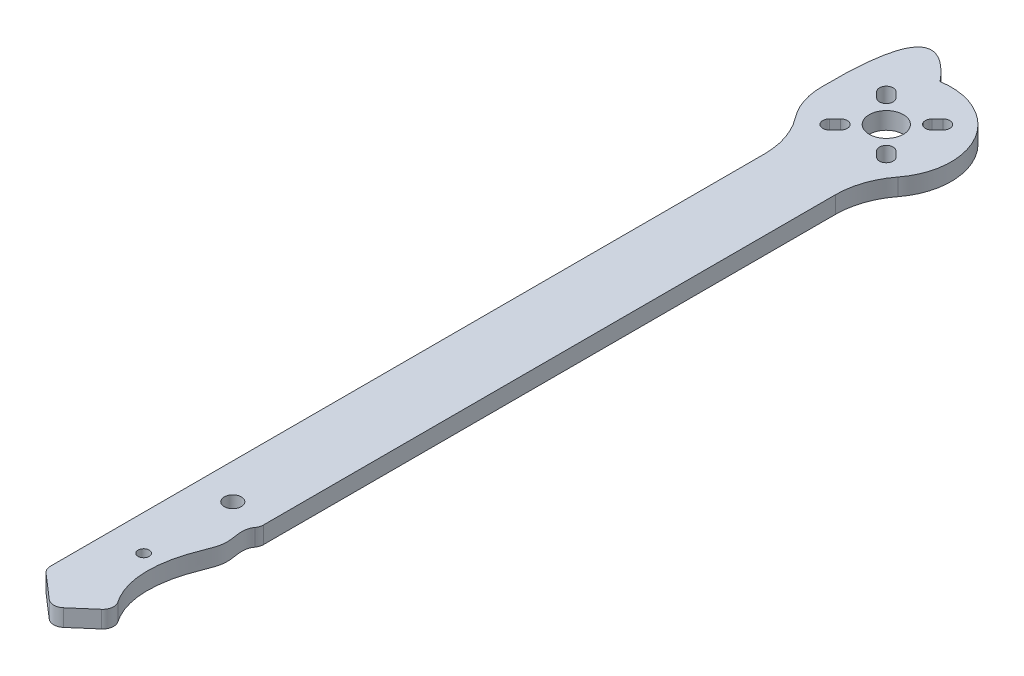
SolidWorks part; units mm, degrees
ref_plane "Front Plane" through (0, 0, 0) normal (0, 0, 1) x (1, 0, 0)
ref_plane "Top Plane" through (0, 0, 0) normal (0, 1, 0) x (1, 0, 0)
ref_plane "Right Plane" through (0, 0, 0) normal (1, 0, 0) x (0, 0, -1)
sketch "Sketch1" plane through (0, 0, 0) normal (0, 1, 0) x (1, 0, 0)
  line L0 (0, 0) -> (0, 209.55)
  line L1 (5.332, 189.1367) -> (6.5949, 187.8739) construction
  line L3 (-8.2352, 181.8344) -> (-8.2352, 0)
  line L4 (-8.2352, 0) -> (8.2352, 0)
  line L5 (8.2352, 181.8344) -> (8.2352, 0)
  line L6 (-6.4546, 190.2593) -> (-7.7174, 188.9964)
  line L7 (6.4546, 190.2593) -> (7.7174, 188.9964)
  line L8 (4.2095, 188.0142) -> (5.4723, 186.7513)
  line L9 (-4.2095, 188.0142) -> (-5.4723, 186.7513)
  line L10 (-5.332, 189.1367) -> (-6.5949, 187.8739) construction
  line L11 (-4.2095, 200.9233) -> (-5.4723, 202.1862)
  line L12 (-6.4546, 198.6782) -> (-7.7174, 199.9411)
  line L13 (-5.332, 199.8008) -> (-6.5949, 201.0636) construction
  line L14 (6.4546, 198.6782) -> (7.7174, 199.9411)
  line L15 (4.2095, 200.9233) -> (5.4723, 202.1862)
  line L16 (5.332, 199.8008) -> (6.5949, 201.0636) construction
  line L17 (-8.2352, 7.1437) -> (0, 0)
  line L18 (8.2352, 7.1437) -> (0, 0)
  line L19 (-8.2352, 7.1437) -> (8.2352, 7.1437)
  circle A0 centre (0, 194.4688) radius 3.9687
  circle A1 centre (0, 194.4688) radius 15.0812
  arc A2 (6.4546, 190.2593) -> (4.2095, 188.0142) centre (5.332, 189.1367) ccw
  arc A3 (5.4723, 186.7513) -> (7.7174, 188.9964) centre (6.5949, 187.8739) ccw
  arc A4 (-4.2095, 188.0142) -> (-6.4546, 190.2593) centre (-5.332, 189.1367) ccw
  arc A5 (-7.7174, 188.9964) -> (-5.4723, 186.7513) centre (-6.5949, 187.8739) ccw
  arc A6 (-6.4546, 198.6782) -> (-4.2095, 200.9233) centre (-5.332, 199.8008) ccw
  arc A7 (-5.4723, 202.1862) -> (-7.7174, 199.9411) centre (-6.5949, 201.0636) ccw
  arc A8 (4.2095, 200.9233) -> (6.4546, 198.6782) centre (5.332, 199.8008) ccw
  arc A9 (7.7174, 199.9411) -> (5.4723, 202.1862) centre (6.5949, 201.0636) ccw
  circle A10 centre (0, 42.4656) radius 1.9844
  circle A11 centre (0, 21.7289) radius 1.2898
  spline S0 degree 2 poles (-15.0812, 194.4688) (-15.5726, 225.0996) (-2.3852, 209.3602) knots 0 0 0 1 1 1
  spline S1 degree 3 poles (8.2352, 40.4439) (6.1597, 38.3778) (8.4485, 34.0777) (3.3122, 23.2306) (2.7642, 13.1947) (8.2352, 7.1437) knots 0 0 0 0 0.202238 0.355836 1 1 1 1
  point P14 (0, 0)
  point P16 (5.9635, 188.5053)
  point P24 (-5.9635, 188.5053)
  point P31 (-5.9635, 200.4322)
  point P38 (5.9635, 200.4322)
  dimension "D2" = 7.9375
  dimension "D6" = 4.9609
  dimension "D8" = 1.9844
  dimension "D11" = 3.9688
  dimension "D12" = 146.05
  dimension "D13" = 2.5797
  dimension "D14" = 17.4625
  dimension "D1" = 209.55
  dimension "D3" = 11.1125
  dimension "D5" = 16.4703
  dimension "D7" = 3.175
  dimension "D9" = 45
  dimension "D17" = 7.1437
  dimension "D4" = 11.1125
  dimension "D10" = 4
extrude "Boss-Extrude1" add sketch "Sketch1" along normal mid plane 3.9688 contours A11 L0 A10 A1 L3 L19 | S1 L5 A1 L0 A10 A11 L19 | L19 L17 L0 | L19 L0 L18 | L0 A1 A0 A7 L11 A6 L12 A5 L6 A4 L9 | L0 A1 A0 A9 L14 A8 L15 A3 L8 A2 L7 | S0 A1
fillet "Fillet1" radius 17.78 2 edges at (-8.2352, 0, -181.8344) (8.2352, 0, -181.8344)
fillet "Fillet3" radius 2.54 4 edges at (8.2352, 0, -40.4439) (-8.2352, 0, -7.1437) (0, 0, 0) (8.2352, 0, -7.1437)
